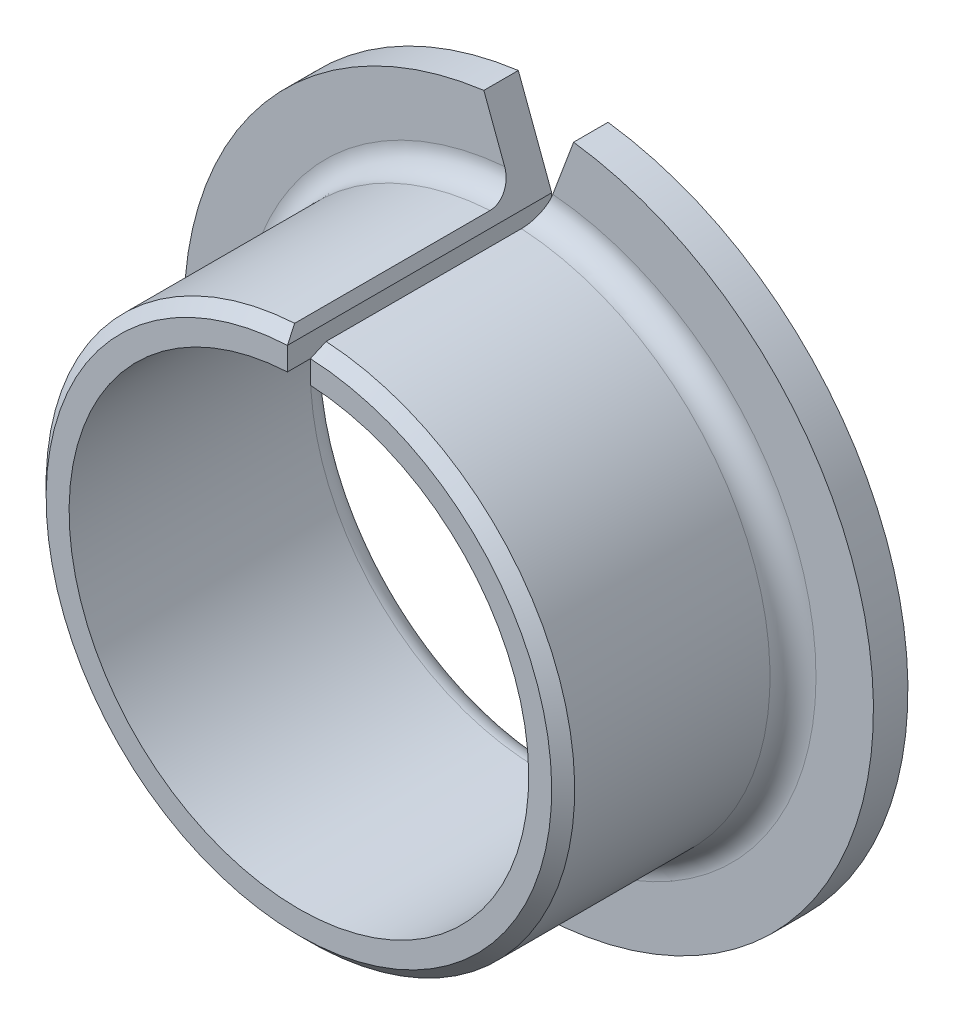
SolidWorks part; units mm, degrees
ref_plane "Plan de face" through (0, 0, 0) normal (0, 0, 1) x (1, 0, 0)
ref_plane "Plan de dessus" through (0, 0, 0) normal (0, 1, 0) x (1, 0, 0)
ref_plane "Plan de droite" through (0, 0, 0) normal (1, 0, 0) x (0, 0, -1)
sketch "Esquisse1" plane through (0, 0, 0) normal (0, 0, 1) x (1, 0, 0)
  circle A0 centre (0, 0) radius 15
extrude "Boss.-Extru.1" add sketch "Esquisse1" along normal blind 11.5
sketch "Esquisse2" plane through (0, 0, 11.5) normal (0, 0, 1) x (1, 0, 0)
  circle A0 centre (0, 0) radius 11.5
extrude "Enlèv. mat.-Extru.1" cut sketch "Esquisse2" against normal blind 10 flip side to cut
sketch "Esquisse3" plane through (0, 0, 11.5) normal (0, 0, 1) x (1, 0, 0)
  circle A0 centre (0, 0) radius 10
extrude "Enlèv. mat.-Extru.2" cut sketch "Esquisse3" against normal up to next
fillet "Congé1" radius 1 1 edges at (11.5, 0, 1.5)
fillet "Congé2" radius 1 1 edges at (10, 0, 0)
sketch "Esquisse4" plane through (0, 0, 11.5) normal (0, 0, 1) x (1, 0, 0)
  line L0 (0, -11.5) -> (0, 15) construction
  line L1 (0.5, 9) -> (-0.5, 9)
  line L2 (0.5, 9) -> (0.5, 10.9886)
  line L3 (-0.5, 9) -> (-0.5, 10.9886)
  line L4 (2, 15) -> (-2, 15)
  line L5 (-2, 15) -> (-0.5, 10.9886)
  line L6 (2, 15) -> (0.5, 10.9886)
  circle A0 centre (0, 0) radius 11.5 construction
  circle A1 centre (0, 0) radius 11.5 construction
  circle A2 centre (0, 0) radius 15 construction
  circle A3 centre (0, 0) radius 11 construction
  point P9 (0.1, -11.5)
  point P10 (0.1, 15)
  point P11 (-0.1, -11.5)
  point P12 (-0.1, 15)
extrude "Enlèv. mat.-Extru.3" cut sketch "Esquisse4" against normal through all
chamfer "Chanfrein1" distance 0.5 angle 45 1 edges at (0, -11.5, 11.5)
